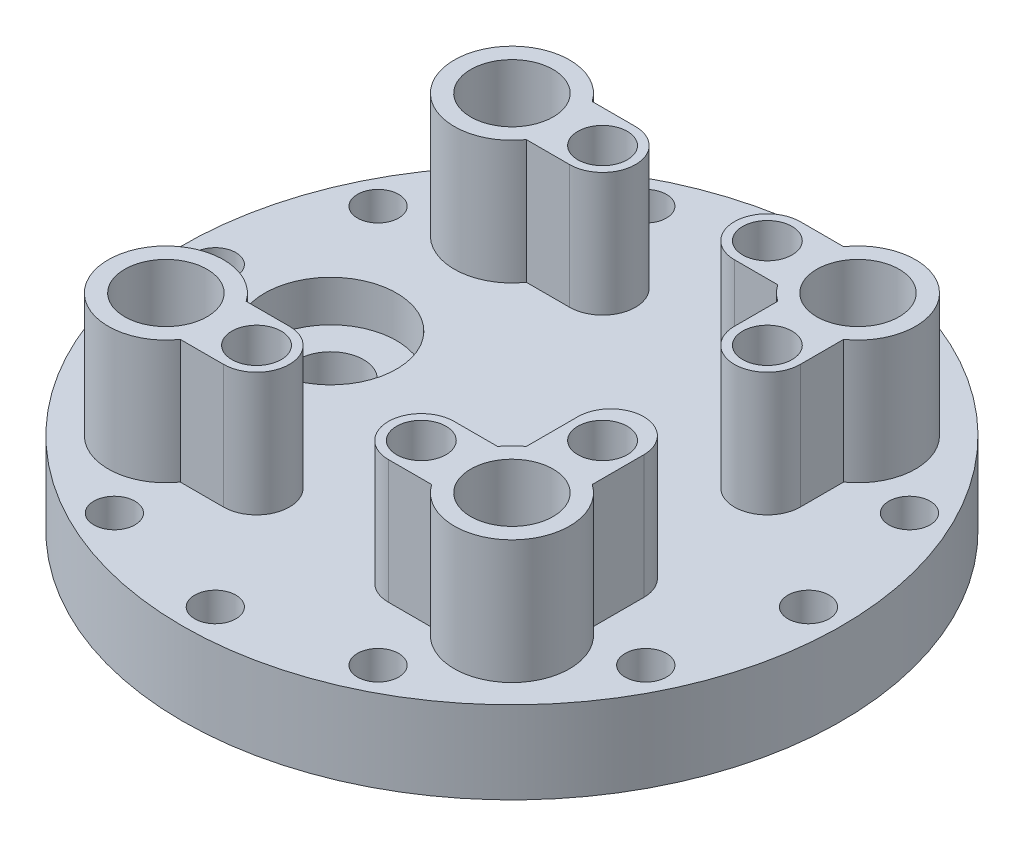
SolidWorks part; units mm, degrees
ref_plane "Front Plane" through (0, 0, 0) normal (0, 0, 1) x (1, 0, 0)
ref_plane "Top Plane" through (0, 0, 0) normal (0, 1, 0) x (1, 0, 0)
ref_plane "Right Plane" through (0, 0, 0) normal (1, 0, 0) x (0, 0, -1)
sketch "Sketch1" plane through (0, 0, 0) normal (0, 1, 0) x (1, 0, 0)
  circle A0 centre (0, 0) radius 40
  circle A40 centre (-21, 21) radius 5
  circle A41 centre (-21, -21) radius 5.0004
  circle A43 centre (21, -21) radius 5
  circle A44 centre (21, 21) radius 5
  circle A45 centre (36, 0) radius 2.5
  circle A47 centre (0, 36) radius 2.5
  circle A48 centre (0, -36) radius 2.5
  circle A49 centre (16, 32.25) radius 2.5
  circle A50 centre (-16, 32.25) radius 2.5
  circle A51 centre (-32.25, 16) radius 2.5
  circle A52 centre (-32.25, -16.005) radius 2.5
  circle A53 centre (-16, -32.25) radius 2.5
  circle A54 centre (16, -32.25) radius 2.5
  circle A55 centre (32.25, 16) radius 2.5
  circle A56 centre (32.25, -16.005) radius 2.5035
  circle A60 centre (-36, 0) radius 2.5
  dimension "D1" = 80
extrude "Boss-Extrude4" add sketch "Sketch1" along normal blind 10
sketch "Sketch2" plane through (0, 10, 0) normal (0, 1, 0) x (1, 0, 0)
  line L0 (0, 0) -> (-22, 0)
  circle A0 centre (-22, 0) radius 4
extrude "Cut-Extrude1" cut sketch "Sketch2" against normal blind 10 contours A0
sketch "Sketch3" plane through (0, 10, 0) normal (0, 1, 0) x (1, 0, 0)
  line L0 (0, 0) -> (-22, 0)
  circle A0 centre (-22, 0) radius 8
extrude "Cut-Extrude2" cut sketch "Sketch3" against normal blind 5 contours A0
sketch "Sketch4" plane through (0, 10, 0) normal (0, 1, 0) x (1, 0, 0)
  line L0 (-10, -17) -> (-15.2554, -17)
  line L1 (-10, -25) -> (-15.2554, -25)
  line L2 (-10, 17) -> (-15.2554, 17)
  line L3 (-10, 25) -> (-15.2554, 25)
  line L4 (10, 25) -> (15.2554, 25)
  line L5 (10, 17) -> (15.2554, 17)
  line L6 (25, 10) -> (25, 15.2554)
  line L7 (17, 10) -> (17, 15.2554)
  line L8 (10, -25) -> (15.2554, -25)
  line L9 (10, -17) -> (15.2554, -17)
  line L10 (25, -9) -> (25, -15.2554)
  line L11 (17, -9) -> (17, -15.2554)
  circle A0 centre (-21, 21) radius 7
  circle A1 centre (-21, -21) radius 7
  circle A2 centre (21, -21) radius 7
  circle A3 centre (21, 21) radius 7
  circle A6 centre (10, -21) radius 3
  circle A8 centre (-10, -21) radius 3
  circle A11 centre (-10, 21) radius 3
  circle A13 centre (10, 21) radius 3
  circle A15 centre (21, 10) radius 3
  circle A17 centre (21, -10) radius 3
  arc A18 (-10, -17) -> (-10, -25) centre (-10, -21) cw
  arc A19 (-10, 25) -> (-10, 17) centre (-10, 21) cw
  arc A20 (10, 17) -> (10, 25) centre (10, 21) cw
  arc A21 (17, 10) -> (25, 10) centre (21, 10) ccw
  arc A22 (10, -25) -> (10, -17) centre (10, -21) cw
  arc A23 (17, -9) -> (25, -9) centre (21, -9) cw
  circle M7 centre (21, 21) radius 5
  circle M8 centre (-21, -21) radius 5.0004
  circle M9 centre (-21, 21) radius 5
  circle M12 centre (21, -21) radius 5
extrude "Boss-Extrude9" add sketch "Sketch4" along normal blind 15 contours A19 L3 A0 L2 A11 | A0 M9 | A1 M8 | A18 L0 A1 L1 A8 | A2 M12 | A22 L8 A2 L9 A6 | A23 L11 A2 L10 A17 | A3 M7 | L7 A21 L6 A3 A15 | A20 L5 A3 L4 A13
